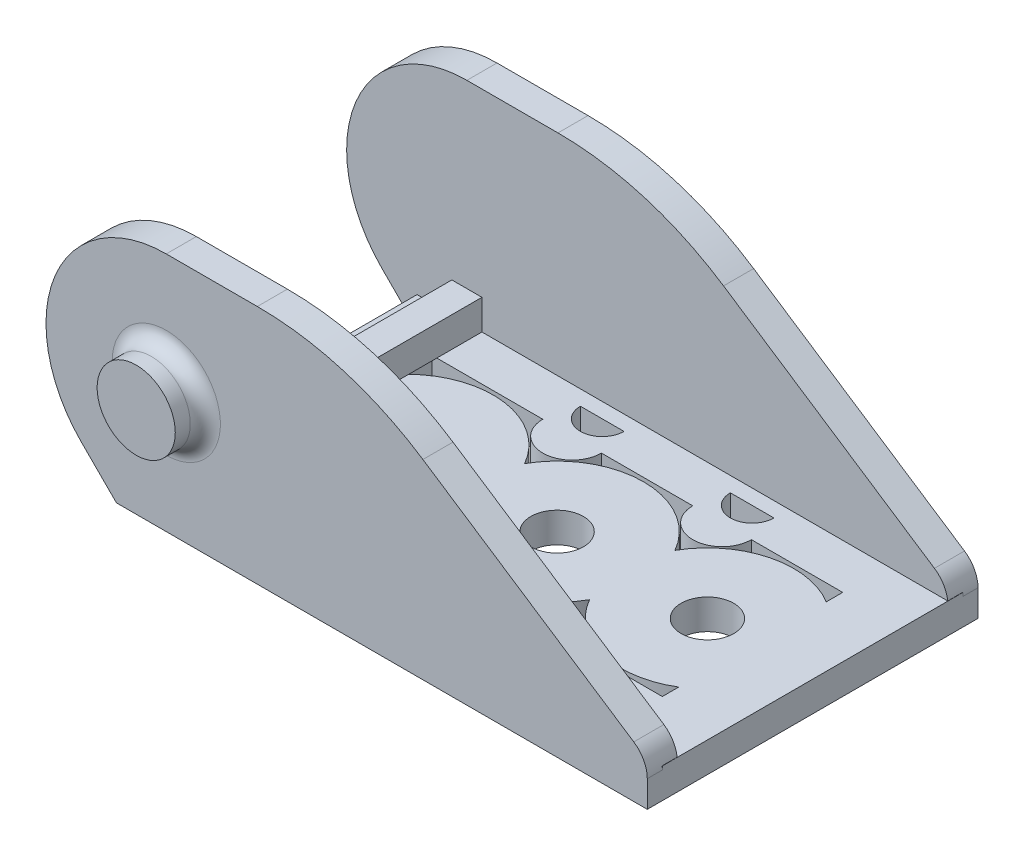
SolidWorks part; units mm, degrees
ref_plane "Front Plane" through (0, 0, 0) normal (0, 0, 1) x (1, 0, 0)
ref_plane "Top Plane" through (0, 0, 0) normal (0, 1, 0) x (1, 0, 0)
ref_plane "Right Plane" through (0, 0, 0) normal (1, 0, 0) x (0, 0, -1)
sketch "Sketch1" plane through (0, 0, 0) normal (0, 1, 0) x (1, 0, 0)
  line L1 (-20, 8) -> (20, 8)
  line L2 (-20, 8) -> (-20, -8)
  line L3 (-20, -8) -> (20, -8)
  line L4 (20, 8) -> (20, -8)
  line L5 (-20, 8) -> (20, -8) construction
  line L6 (-20, -8) -> (20, 8) construction
  point P0 (0, 0)
sketch "Sketch3" plane through (0, 0, 0) normal (0, 0, 1) x (1, 0, 0)
  line L0 (-20, 0) -> (20, 0) construction
  line L1 (-12, 0) -> (12, 0)
  line L2 (-20, 0) -> (-20, 16) construction
  line L3 (-12, 16) -> (12, 16)
  line L5 (-20, 0) -> (20, 0) construction
  line L6 (-20, 8) -> (-12, 8) construction
  line L7 (20, 8) -> (12, 8) construction
  arc A0 (-12, 16) -> (-12, 0) centre (-12, 8) ccw
  arc A1 (12, 0) -> (12, 16) centre (12, 8) ccw
ref_plane "Plane1" through (0, 0, 9) normal (0, 0, 1) x (1, 0, 0)
sketch "Sketch6" plane through (0, 0, 0) normal (0, 1, 0) x (1, 0, 0)
  line L0 (0, 0) -> (0, -9) construction
  line L1 (-20, -13) -> (20, -13.5) construction
  line L2 (-20, -13) -> (-20, -11) construction
  line L3 (20, -9) -> (20, -11)
  line L4 (-20, -11) -> (20, -11)
  line L5 (0, -11) -> (0, -13) construction
  line L10 (1, -11.5) -> (1, -13) construction
  line L11 (-20, -11) -> (-20, -9)
  line L12 (-20, -9) -> (20, -9)
extrude "Boss-Extrude4" add sketch "Sketch6" along normal blind 16
sketch "Sketch8" plane through (0, 0, 11) normal (0, 0, 1) x (1, 0, 0)
  circle A1 centre (-12, 8) radius 2.6
extrude "Boss-Extrude5" add sketch "Sketch8" along normal blind 2
fillet "Fillet1" radius 1 1 edges at (-14.6, 8, 11)
sketch "Sketch7" plane through (0, 0, 11) normal (0, 0, 1) x (1, 0, 0)
  line L0 (-5.942, 16) -> (-12, 16)
  line L1 (-15.3137, 0) -> (20, 0)
  line L2 (-17.6569, 2.3431) -> (-15.3137, 0)
  line L3 (21.3543, 17.091) -> (-21.3543, 17.091)
  line L4 (21.3543, 17.091) -> (21.3543, -1.091)
  line L5 (21.3543, -1.091) -> (-21.3543, -1.091)
  line L6 (-21.3543, 17.091) -> (-21.3543, -1.091)
  line L7 (21.3543, 17.091) -> (-21.3543, -1.091) construction
  line L8 (21.3543, -1.091) -> (-21.3543, 17.091) construction
  line L9 (20, 0) -> (20, 1.7672)
  line L11 (19.1015, 3.4366) -> (5.0731, 12.6933)
  line L14 (-0.0619, 0) -> (-0.0619, 3.8657) construction
  arc A1 (-12, 16) -> (-17.6569, 2.3431) centre (-12, 8) ccw
  arc A2 (5.0731, 12.6933) -> (-5.942, 16) centre (-5.942, -4) ccw
  arc A3 (20, 1.7672) -> (19.1015, 3.4366) centre (18, 1.7672) ccw
  point P6 (0, 8)
  point P20 (20, 2.8437)
  point P26 (0.0619, 16)
extrude "Cut-Extrude1" cut sketch "Sketch7" along normal through all and the other way blind 16
mirror "Mirror2" about plane through (0, 0, 0) normal (0, 0, 1) of bodies 115 109
sketch "Sketch14" plane through (0, 0, 0) normal (0, 1, 0) x (1, 0, 0)
  line L0 (-0.0619, -10) -> (1.9113, -10.7141) construction
  line L1 (16, 6) -> (9.9255, 6)
  line L2 (16, 4.9054) -> (16, 6)
  line L3 (-11.3137, -6) -> (-11.3137, -3.8019)
  line L4 (-11.3137, -6) -> (-3.95, -6)
  line L5 (0.4647, 6) -> (-11.3137, 6) construction
  line L6 (16, -8.5) -> (16, 8.5) construction
  line L7 (-11.3137, 3.8019) -> (-11.3137, 6)
  line L8 (16, -6) -> (16, -4.9054)
  line L9 (-11.3137, -6) -> (-11.3137, 6) construction
  line L10 (5.9017, 12.5) -> (2.696, 11.3622) construction
  line L11 (6.5905, 8.5) -> (4.6969, 7.8279) construction
  line L12 (-15.3137, -10) -> (-15.3137, 10)
  line L13 (20, -10) -> (20, 10)
  line L14 (20, 0) -> (13, 0) construction
  line L15 (16, 8.5) -> (6.5905, 8.5) construction
  line L16 (2.696, -11.3622) -> (5.9017, -12.5) construction
  line L17 (13, 0) -> (3, 0) construction
  line L18 (3, 0) -> (-7, 0) construction
  line L19 (-11.3137, -6) -> (0.6397, -6) construction
  line L20 (4.6991, -7.8287) -> (6.5905, -8.5) construction
  line L21 (6.5905, -8.5) -> (16, -8.5) construction
  line L22 (2.696, 11.3622) -> (2.0472, 10.8275) construction
  line L23 (-15.3137, -10) -> (-0.0619, -10) construction
  line L24 (20, 10) -> (-15.3137, 10)
  line L25 (4.6969, 7.8279) -> (4.0584, 7.3017) construction
  line L26 (-15.3137, -10) -> (20, -10)
  line L27 (1.9113, -10.7141) -> (2.696, -11.3622) construction
  line L28 (3.9243, -7.1887) -> (4.6991, -7.8287) construction
  line L29 (2.0472, 10.8275) -> (-0.2374, 10) construction
  line L30 (4.0584, 7.3017) -> (0.4647, 6) construction
  line L31 (0.6397, -6) -> (3.9243, -7.1887) construction
  line L32 (5.9017, -12.5) -> (20, -12.5) construction
  line L33 (20, 12.5) -> (5.9017, 12.5) construction
  line L34 (-0.2374, 10) -> (-15.3137, 10) construction
  line L35 (20, -12.5) -> (20, 12.5) construction
  line L36 (-3.9509, 6) -> (-11.3137, 6)
  line L37 (6.0255, 6) -> (-0.0491, 6)
  line L38 (-0.05, -6) -> (6.05, -6)
  line L39 (9.95, -6) -> (16, -6)
  line L40 (9.4255, 8) -> (6.5255, 8)
  line L42 (-3.45, -8) -> (-0.55, -8)
  line L44 (18, 8) -> (-13.3137, 8) construction
  line L45 (-0.55, 8) -> (-3.45, 8)
  line L46 (-13.3137, -8) -> (18, -8) construction
  line L47 (6.55, -8) -> (9.45, -8)
  line L48 (18, -8) -> (18, 8) construction
  line L49 (-13.3137, -8) -> (-13.3137, 8) construction
  circle A0 centre (13, 0) radius 1.75
  circle A1 centre (3, 0) radius 1.75
  circle A2 centre (-7, 0) radius 1.75
  arc A3 (-2, 2.8395) -> (-11.3137, 3.8019) centre (-7, 0) ccw
  arc A4 (-2, -2.8395) -> (8, -2.8395) centre (3, 0) ccw
  arc A5 (8, -2.8395) -> (16, -4.9054) centre (13, 0) ccw
  circle A6 centre (3, 0) radius 5.75 construction
  circle A7 centre (-7, 0) radius 5.75 construction
  circle A8 centre (13, 0) radius 5.75 construction
  arc A9 (8, 2.8395) -> (-2, 2.8395) centre (3, 0) ccw
  arc A10 (16, 4.9054) -> (8, 2.8395) centre (13, 0) ccw
  arc A11 (-11.3137, -3.8019) -> (-2, -2.8395) centre (-7, 0) ccw
  arc A12 (-3.9509, 6) -> (-0.0491, 6) centre (-2, 6) ccw
  arc A13 (6.0255, 6) -> (9.9255, 6) centre (7.9755, 6) ccw
  arc A14 (-0.05, -6) -> (-3.95, -6) centre (-2, -6) ccw
  arc A15 (9.95, -6) -> (6.05, -6) centre (8, -6) ccw
  arc A16 (-3.45, 8) -> (-0.55, 8) centre (-2, 8) ccw
  arc A17 (6.5255, 8) -> (9.4255, 8) centre (7.9755, 8) ccw
  arc A18 (-0.55, -8) -> (-3.45, -8) centre (-2, -8) ccw
  arc A19 (9.45, -8) -> (6.55, -8) centre (8, -8) ccw
  dimension "D1" = 4
  dimension "D3" = 2
  dimension "D2" = 4
extrude "Boss-Extrude8" add sketch "Sketch14" along normal blind 2
sketch "Sketch15" plane through (0, 2, 0) normal (0, 1, 0) x (1, 0, 0)
  line L0 (1.25, 0) -> (-5.25, 0) construction
  line L1 (-12, 9) -> (-12, -9)
  circle A0 centre (3, 0) radius 1.75 construction
  circle A1 centre (-7, 0) radius 1.75 construction
extrude "Extrude-Thin1" add sketch "Sketch15" along normal blind 2 thin thin type mid plane wall 2
